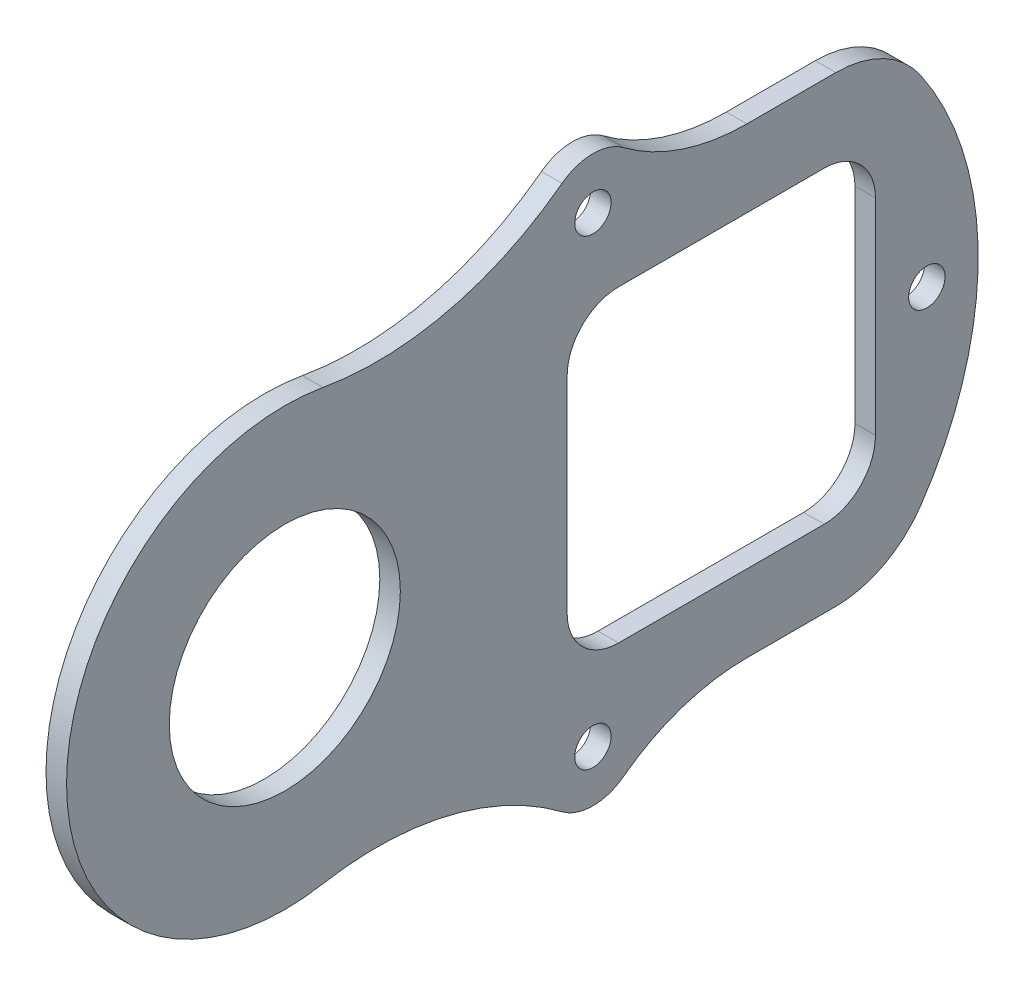
SolidWorks part; units mm, degrees
ref_plane "Front" through (0, 0, 0) normal (0, 0, 1) x (1, 0, 0)
ref_plane "Top" through (0, 0, 0) normal (0, 1, 0) x (1, 0, 0)
ref_plane "Right" through (0, 0, 0) normal (1, 0, 0) x (0, 0, -1)
sketch "Sketch1" plane through (0, 0, 0) normal (1, 0, 0) x (0, 0, -1)
  line L7 (41.2623, 19.0627) -> (66.6877, 19.0627)
  line L8 (38.0873, 15.8877) -> (69.8627, 15.8877) construction
  line L9 (66.6877, -12.7127) -> (74.5454, -20.5704) construction
  line L10 (38.1, 28.575) -> (38.1, -28.575) construction
  line L11 (38.0873, 15.8877) -> (38.0873, -15.8877) construction
  line L12 (38.0873, -15.8877) -> (69.8627, -15.8877) construction
  line L13 (69.8627, 15.8877) -> (69.8627, -15.8877) construction
  line L14 (73.0377, 12.7127) -> (73.0377, -12.7127)
  line L15 (41.2623, -19.0627) -> (66.6877, -19.0627)
  line L16 (34.9123, 12.7127) -> (34.9123, -12.7127)
  line L17 (34.9123, 19.0627) -> (73.0377, 19.0627) construction
  line L18 (73.0377, 19.0627) -> (73.0377, -19.0627) construction
  line L19 (34.9123, -19.0627) -> (73.0377, -19.0627) construction
  line L20 (34.9123, 19.0627) -> (34.9123, -19.0627) construction
  line L21 (57.1331, -28.5877) -> (68.1325, -28.5877)
  line L22 (57.1331, 28.5877) -> (68.1325, 28.5877)
  circle A0 centre (0, 0) radius 14.2875
  circle A1 centre (0, 0) radius 14.2875 construction
  arc A2 (4.713, 26.5728) -> (4.713, -26.5728) centre (0, 0) ccw
  arc A5 (34.2809, -33.6482) -> (41.9066, -33.6575) centre (38.1, -28.575) ccw
  arc A6 (41.9066, 33.6575) -> (34.2809, 33.6482) centre (38.1, 28.575) ccw
  arc A8 (34.2809, -33.6482) -> (4.713, -26.5728) centre (11.3665, -64.0873) ccw
  circle A10 centre (64.9351, -10.9601) radius 6.35 construction
  circle A11 centre (64.9351, -10.9601) radius 1.7526 construction
  circle A12 centre (64.9351, 10.9601) radius 6.35 construction
  circle A13 centre (64.9351, 10.9601) radius 1.7526 construction
  arc A15 (4.713, 26.5728) -> (34.2809, 33.6482) centre (11.3665, 64.0873) ccw
  arc A17 (66.6877, 19.0627) -> (73.0377, 12.7127) centre (66.6877, 12.7127) cw
  arc A18 (73.0377, -12.7127) -> (66.6877, -19.0627) centre (66.6877, -12.7127) cw
  arc A19 (41.2623, -19.0627) -> (34.9123, -12.7127) centre (41.2623, -12.7127) cw
  arc A20 (41.2623, 19.0627) -> (34.9123, 12.7127) centre (41.2623, 12.7127) ccw
  circle A21 centre (79.3877, 0) radius 6.35 construction
  arc A22 (41.9066, 33.6575) -> (57.1331, 28.5877) centre (57.1331, 53.9877) ccw
  arc A23 (57.1331, -28.5877) -> (41.9066, -33.6575) centre (57.1331, -53.9877) ccw
  arc A24 (78.622, -23.0473) -> (78.622, 23.0473) centre (44.8554, 0) ccw
  circle A25 centre (74.5454, -20.5704) radius 4.7625 construction
  circle A26 centre (74.5454, 20.5704) radius 4.7625 construction
  arc A27 (68.1325, 28.5877) -> (78.622, 23.0473) centre (68.1325, 15.8877) cw
  arc A28 (68.1325, -28.5877) -> (78.622, -23.0473) centre (68.1325, -15.8877) ccw
  point P3 (69.8627, 0)
  point P22 (38.1, 0)
  dimension "D1" = 12.7
  dimension "D4" = 4.9276
  dimension "D6" = 9.525
  dimension "D3" = 76.2
  dimension "D8" = 38.1
  dimension "D9" = 12.7
  dimension "D10" = 3.175
  dimension "D11" = 6.35
  dimension "D7" = 25.4
  dimension "D13" = 9.525
  dimension "D14" = 6.35
  dimension "D15" = 12.7
  dimension "D2" = 4.9276
  dimension "D5" = 57.15
  dimension "D12" = 9.525
extrude "Boss-Extrude1" add sketch "Sketch1" along normal blind 2.54
hole_wizard "#8 Clearance Hole1" positions "Sketch2" profile "Sketch3" hole size "#8" standard "ANSI Inch" end condition through all
sketch "Sketch2" plane through (2.54, 0, 0) normal (1, 0, 0) x (0, 0, -1)
  point P0 (38.1, 28.575)
  point P2 (79.3877, 0)
  point P4 (38.1, -28.575)
sketch "Sketch3" plane through (2.54, 28.575, -38.1) normal (0, 1, 0) x (0, 0, -1)
  line L0 (0, 0) -> (0, 2.54)
  line L1 (0, 2.54) -> (2.2479, 2.54)
  line L2 (2.2479, 2.54) -> (2.2479, 0)
  line L5 (2.2479, 0) -> (0, 0)
  line L11 (0, -6.35) -> (0, 107.95) construction
  dimension "Thru Hole Dia." = 4.4958
  dimension "Thru Hole Depth" = 2.54
